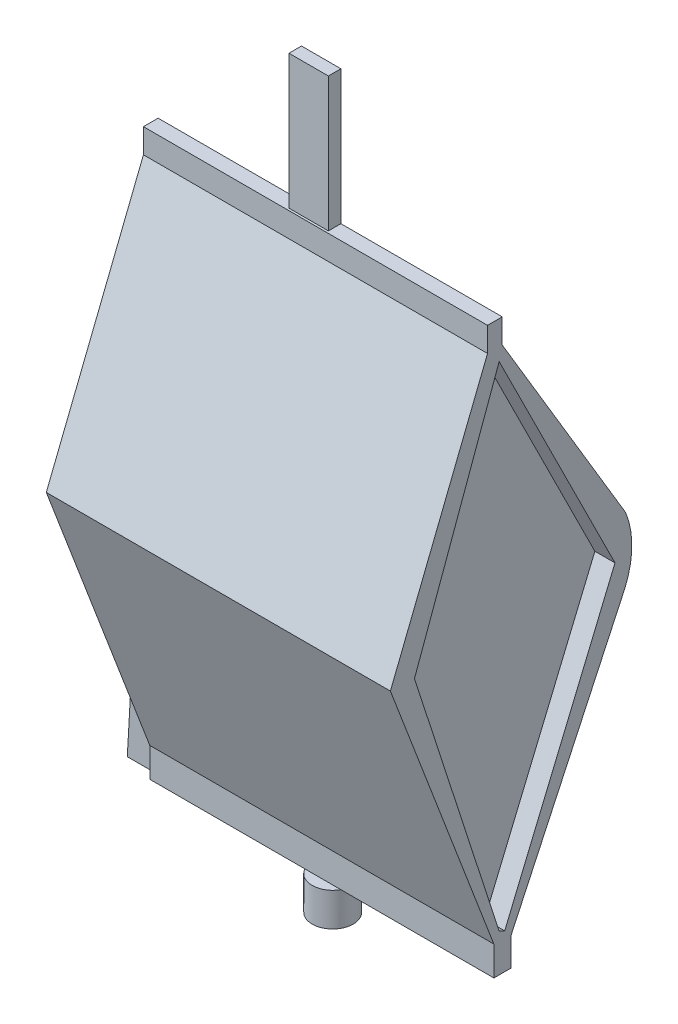
SolidWorks part; units mm, degrees
ref_plane "Front Plane" through (0, 0, 0) normal (0, 0, 1) x (1, 0, 0)
ref_plane "Top Plane" through (0, 0, 0) normal (0, 1, 0) x (1, 0, 0)
ref_plane "Right Plane" through (0, 0, 0) normal (1, 0, 0) x (0, 0, -1)
sketch "Sketch4" plane through (0, 0, 0) normal (0, 0, 1) x (1, 0, 0)
  line L1 (-31.4181, 42.3611) -> (31.4181, 42.3611)
  line L2 (-31.4181, 42.3611) -> (-31.4181, -42.3611)
  line L3 (-31.4181, -42.3611) -> (31.4181, -42.3611)
  line L4 (31.4181, 42.3611) -> (31.4181, -42.3611)
  line L5 (-31.4181, 42.3611) -> (31.4181, -42.3611) construction
  line L6 (-31.4181, -42.3611) -> (31.4181, 42.3611) construction
  point P0 (0, 0)
extrude "Boss-Extrude2" add sketch "Sketch4" along normal blind 50
sketch "Sketch5" plane through (31.4181, 0, 0) normal (1, 0, 0) x (0, 0, -1)
  line L0 (-31.846, 42.3611) -> (-33.6642, 67.8538)
  line L1 (-50, 42.3611) -> (0, 42.3611) construction
  line L2 (-46.3223, 2.3889) -> (-30.8984, -37.9824)
  line L3 (-30.8984, -37.9824) -> (-30.8984, -42.3611)
  line L4 (-50, -42.3611) -> (0, -42.3611) construction
  line L6 (-29.0687, -42.3611) -> (-29.0687, -37.9824)
  line L7 (-29.0687, -37.9824) -> (-13.2397, 2.3889)
  line L8 (-13.2397, 2.3889) -> (-28.1509, 38.7282)
  line L9 (-28.1509, 38.7282) -> (-28.1509, 42.3611)
  line L11 (-31.846, 42.3611) -> (-31.846, 38.7282)
  line L12 (-31.846, 38.7282) -> (-46.3223, 2.3889)
  line L13 (-33.6642, 67.8538) -> (-71.791, 67.8538)
  line L14 (-71.791, 67.8538) -> (-78.4638, -46.7769)
  line L15 (-78.4638, -46.7769) -> (-30.8035, -45.1607)
  line L16 (-30.8035, -45.1607) -> (-30.8984, -42.3611)
  line M12 (0, 42.3611) -> (-50, 42.3611)
  line M13 (-50, 42.3611) -> (-50, -42.3611)
  line M14 (-50, -42.3611) -> (0, -42.3611)
extrude "Cut-Extrude2" cut sketch "Sketch5" against normal blind 80 contours L12 L11 L3 L2 M12 M13 M14
sketch "Sketch6" plane through (31.4181, 0, 0) normal (1, 0, 0) x (0, 0, -1)
  line L0 (-29.6554, 42.3611) -> (-29.6554, 38.7226)
  line L1 (-31.846, 42.3611) -> (0, 42.3611) construction
  line L2 (-29.6554, 38.7226) -> (-8.7764, 3.7502)
  line L3 (-8.7764, 3.7502) -> (-28.3285, -38.1177)
  line L4 (-28.3285, -38.1177) -> (-28.3285, -42.3611)
  line L5 (-30.8984, -42.3611) -> (0, -42.3611) construction
  line L6 (-28.3285, -42.3611) -> (-27.6775, -46.6259)
  line L7 (-27.6775, -46.6259) -> (16.8398, -52.0454)
  line L8 (16.8398, -52.0454) -> (10.2677, 27.1903)
  line L9 (10.2677, 27.1903) -> (3.7395, 54.484)
  line L10 (3.7395, 54.484) -> (-29.6554, 42.3611)
extrude "Cut-Extrude3" cut sketch "Sketch6" against normal blind 80
sketch "Sketch7" plane through (-31.4181, 0, 0) normal (-1, 0, 0) x (0, 0, 1)
  line L1 (29.6554, 38.7226) -> (8.7764, 3.7502) construction
  line L2 (8.7764, 3.7502) -> (28.3285, -38.1177) construction
  arc A0 (13.2289, 11.2081) -> (11.7109, -2.5336) centre (22.9458, 3.18) ccw
  arc A1 (13.2289, 11.2081) -> (11.7109, -2.5336) centre (8.6224, 4.7623) ccw
extrude "Cut-Extrude5" cut sketch "Sketch7" against normal blind 80
sketch "Sketch8" plane through (31.4181, 0, 0) normal (1, 0, 0) x (0, 0, -1)
  line L0 (-30.1116, 36.8174) -> (-42.7351, 2.196)
  line L1 (-42.7351, 2.196) -> (-30.1116, -36.6941)
  line L2 (-30.1116, -36.6941) -> (-29.2891, -37.0782)
  line L3 (-29.2891, -37.0782) -> (-12.8456, 2.196)
  line L4 (-12.8456, 2.196) -> (-30.1116, 36.8174)
extrude "Cut-Extrude6" cut sketch "Sketch8" against normal blind 3
sketch "Sketch9" plane through (0, 0, 29.6554) normal (0, 0, -1) x (-1, 0, 0)
  line L0 (19.8699, 42.3611) -> (19.8699, 38.7226)
  line L1 (31.4181, 42.3611) -> (-31.4181, 42.3611) construction
  line L2 (31.4181, 38.7226) -> (-31.4181, 38.7226) construction
  line L3 (19.8699, 38.7226) -> (19.8699, 5.587)
  line L4 (19.8699, 5.587) -> (19.8699, -4.1869)
  line L5 (19.8699, -4.1869) -> (19.8699, -38.2085)
  line L6 (19.8699, -38.2085) -> (19.8699, -42.0598)
  line L7 (19.8699, -42.0598) -> (19.8699, -47.0269)
  line L8 (19.8699, -47.0269) -> (41.2567, -49.5859)
  line L9 (41.2567, -49.5859) -> (42.0813, -21.1977)
  line L10 (42.0813, -21.1977) -> (42.0813, 12.4282)
  line L11 (42.0813, 12.4282) -> (37.4822, 37.5131)
  line L12 (37.4822, 37.5131) -> (31.4181, 49.4838)
  line L13 (31.4181, 49.4838) -> (19.8699, 42.3611)
extrude "Cut-Extrude8" cut sketch "Sketch9" against normal blind 80
sketch "Sketch10" plane through (0, -2.8774, 4.8197) normal (0, 0.5126, -0.8586) x (-1, 0, 0)
  line L0 (19.8699, 48.4497) -> (25.6937, -39.8033)
  line L1 (25.6937, -39.8033) -> (32.4481, -43.4448)
  line L2 (32.4481, -43.4448) -> (49.8026, -43.4448)
  line L3 (49.8026, -43.4448) -> (32.4481, 57.8409)
  line L4 (32.4481, 57.8409) -> (19.8699, 48.4497)
extrude "Cut-Extrude9" cut sketch "Sketch10" against normal blind 80
sketch "Sketch11" plane through (0, 42.3611, 0) normal (0, 1, 0) x (1, 0, 0)
  line L0 (-19.8699, -29.6554) -> (31.4181, -29.6554) construction
  line L1 (7.3729, -31.5211) -> (1.502, -31.5211)
  line L2 (7.3729, -31.5211) -> (7.3729, -29.6554)
  line L3 (7.3729, -29.6554) -> (1.502, -29.6554)
  line L4 (1.502, -31.5211) -> (1.502, -29.6554)
  line L5 (7.3729, -31.5211) -> (1.502, -29.6554) construction
  line L6 (7.3729, -29.6554) -> (1.502, -31.5211) construction
  point P0 (4.4374, -30.5883)
extrude "Boss-Extrude3" add sketch "Sketch11" along normal blind 20
scale "Scale1" scale about centroid uniform scaling yes scale factor 0.5
scale "Scale2" scale about centroid uniform scaling yes scale factor 0.4
scale "Scale3" scale about centroid uniform scaling yes scale factor 0.5
scale "Scale4" scale about centroid uniform scaling yes scale factor 1
scale "Scale5" scale about centroid uniform scaling yes scale factor 4
sketch "Sketch13" plane through (0, -16.3833, 0) normal (0, -1, 0) x (-1, 0, 0)
  circle A0 centre (-4.7978, -28.8176) radius 1.2211
extrude "Boss-Extrude4" add sketch "Sketch13" along normal blind 2
